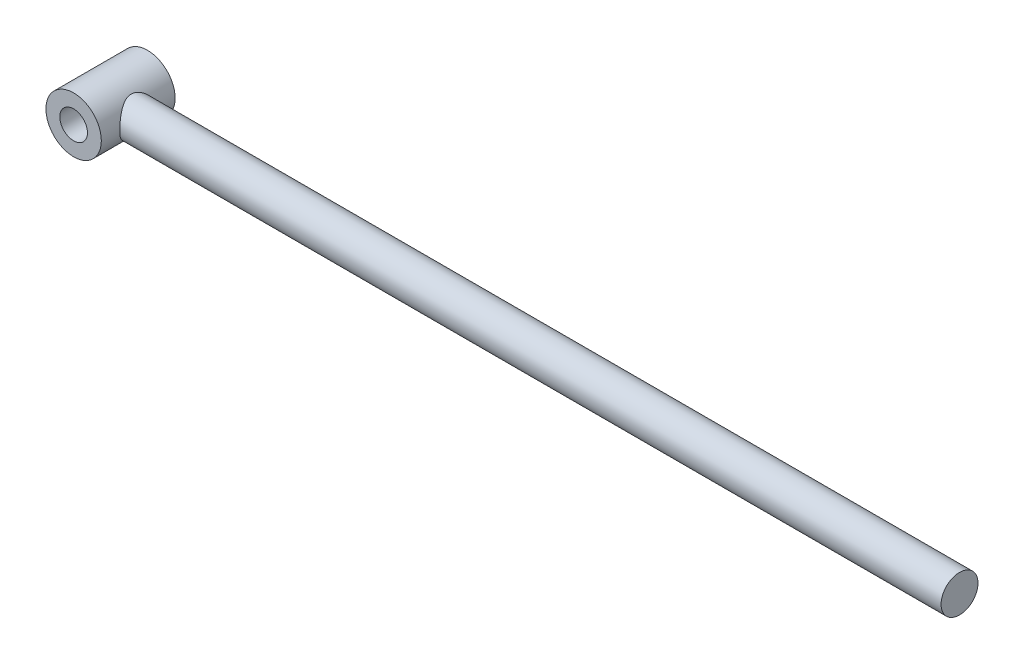
SolidWorks part; units mm, degrees
ref_plane "Front Plane" through (0, 0, 0) normal (0, 0, 1) x (1, 0, 0)
ref_plane "Top Plane" through (0, 0, 0) normal (0, 1, 0) x (1, 0, 0)
ref_plane "Right Plane" through (0, 0, 0) normal (1, 0, 0) x (0, 0, -1)
sketch "Sketch1" plane through (0, 0, 0) normal (0, 0, 1) x (1, 0, 0)
  circle A0 centre (0, 0) radius 15
  circle A1 centre (0, 0) radius 30
  dimension "D1" = 30
  dimension "D2" = 15
extrude "Boss-Extrude1" add sketch "Sketch1" along normal mid plane 80
ref_plane "Plane1" through (20, 0, 0) normal (1, 0, 0) x (0, 0, -1)
sketch "Sketch2" plane through (20, 0, 0) normal (1, 0, 0) x (0, 0, -1)
  circle A0 centre (0, 0) radius 20
  dimension "D1" = 40
extrude "Boss-Extrude2" add sketch "Sketch2" along normal blind 900
